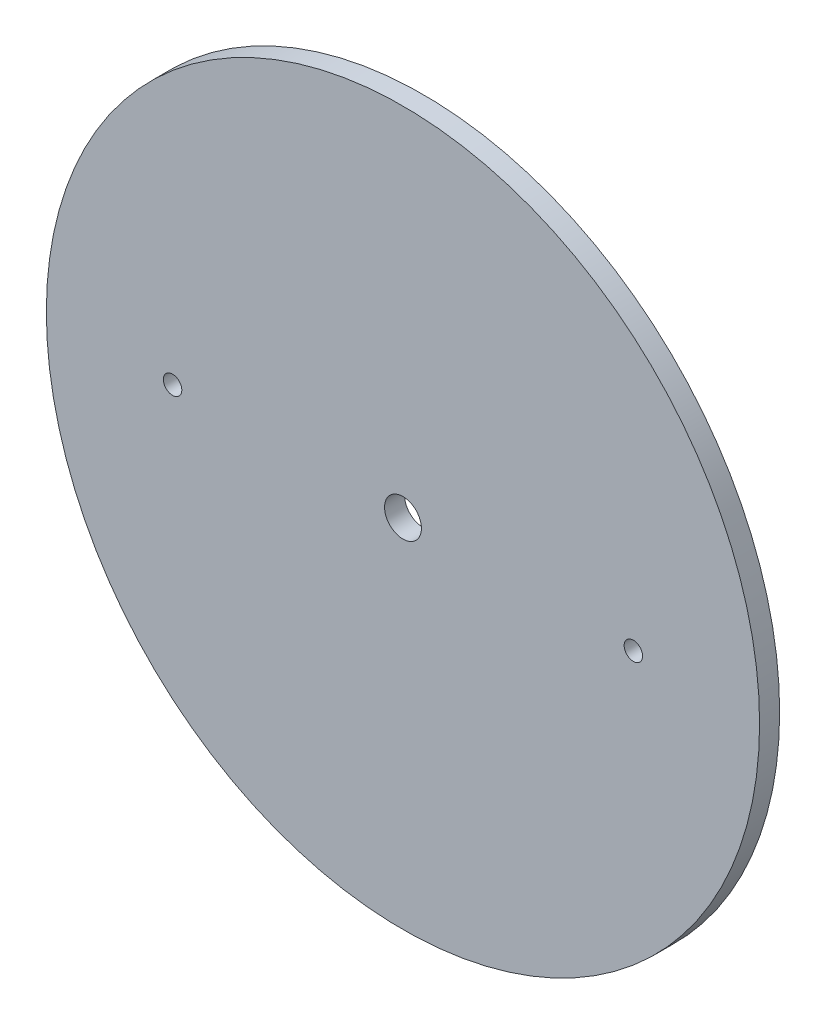
SolidWorks part; units mm, degrees
material "1060 Alloy"
ref_plane "Front Plane" through (0, 0, 0) normal (0, 0, 1) x (1, 0, 0)
ref_plane "Top Plane" through (0, 0, 0) normal (0, 1, 0) x (1, 0, 0)
ref_plane "Right Plane" through (0, 0, 0) normal (1, 0, 0) x (0, 0, -1)
ref_plane "Plane1" through (0, 0, -5) normal (0, 0, -1) x (-1, 0, 0)
sketch "Sketch1" plane through (0, 0, -5) normal (0, 0, -1) x (-1, 0, 0)
  circle A0 centre (45.9318, 0) radius 1.8373
  circle A1 centre (-45.9318, 0) radius 1.8373
  circle A2 centre (0, 0) radius 3.6745
  circle A3 centre (0, 0) radius 71.1
  dimension "D1" = 142.2
extrude "Boss-Extrude1" add sketch "Sketch1" against normal blind 4
